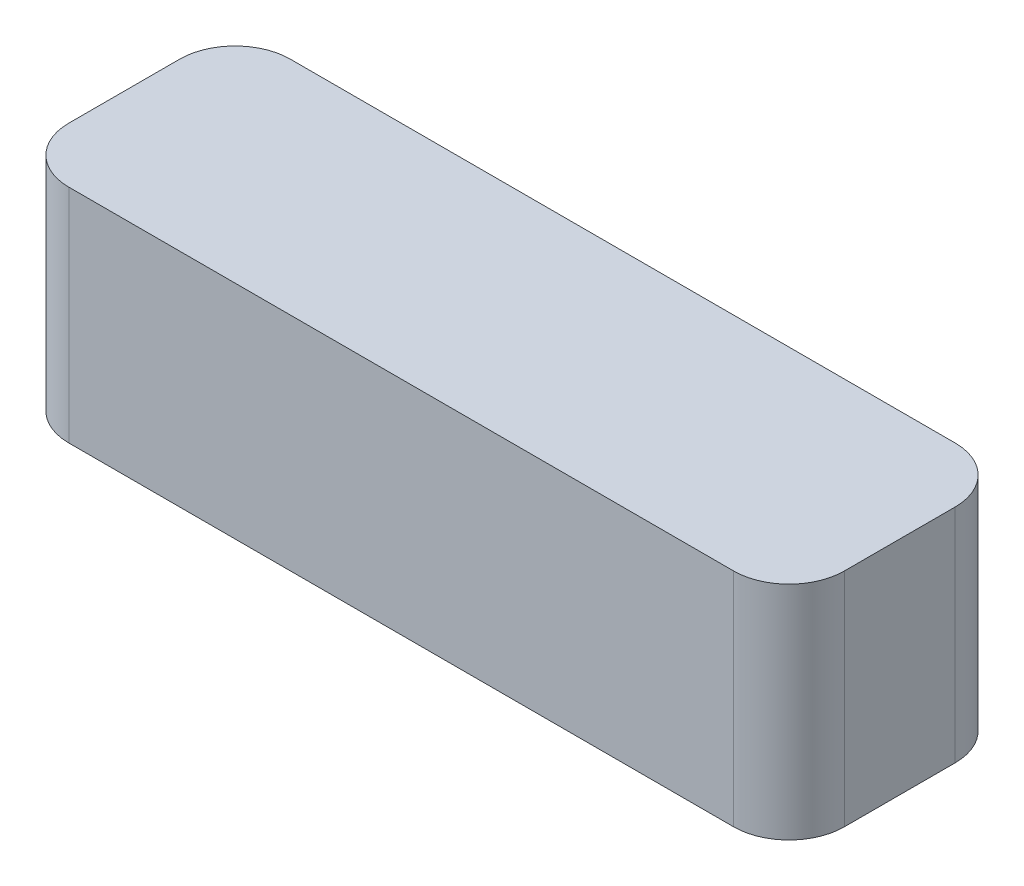
SolidWorks part; units mm, degrees
ref_plane "前视基准面" through (0, 0, 0) normal (0, 0, 1) x (1, 0, 0)
ref_plane "上视基准面" through (0, 0, 0) normal (0, 1, 0) x (1, 0, 0)
ref_plane "右视基准面" through (0, 0, 0) normal (1, 0, 0) x (0, 0, -1)
sketch "Sketch1" plane through (0, 0, 0) normal (0, 1, 0) x (1, 0, 0)
  line L1 (-6, 2) -> (6, 2)
  line L2 (-7, 1) -> (-7, -1)
  line L3 (-6, -2) -> (6, -2)
  line L4 (7, 1) -> (7, -1)
  line L5 (-7, 2) -> (7, -2) construction
  line L6 (-7, -2) -> (7, 2) construction
  arc A0 (6, 2) -> (7, 1) centre (6, 1) cw
  arc A1 (6, -2) -> (7, -1) centre (6, -1) ccw
  arc A2 (-7, -1) -> (-6, -2) centre (-6, -1) ccw
  arc A3 (-6, 2) -> (-7, 1) centre (-6, 1) ccw
  point P0 (0, 0)
  dimension "D3" = 1
  dimension "D1" = 14
  dimension "D2" = 4
extrude "Boss-Extrude1" add sketch "Sketch1" along normal blind 4
